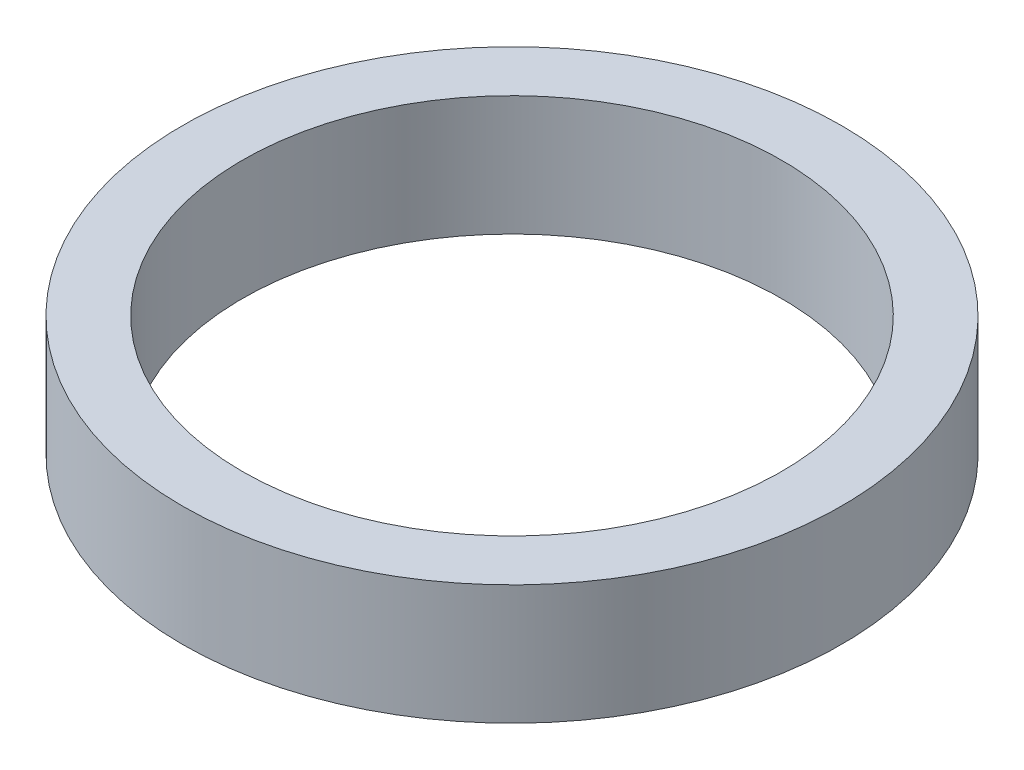
SolidWorks part; units mm, degrees
ref_plane "Front Plane" through (0, 0, 0) normal (0, 0, 1) x (1, 0, 0)
ref_plane "Top Plane" through (0, 0, 0) normal (0, 1, 0) x (1, 0, 0)
ref_plane "Right Plane" through (0, 0, 0) normal (1, 0, 0) x (0, 0, -1)
sketch "Sketch1" plane through (0, 0, 0) normal (0, 1, 0) x (1, 0, 0)
  circle A0 centre (0, 0) radius 13.97
extrude "Boss-Extrude1" add sketch "Sketch1" along normal blind 5.08
sketch "Sketch2" plane through (0, 5.08, 0) normal (0, 1, 0) x (1, 0, 0)
  circle A0 centre (0, 0) radius 11.43
extrude "Cut-Extrude1" cut sketch "Sketch2" against normal blind 5.08
